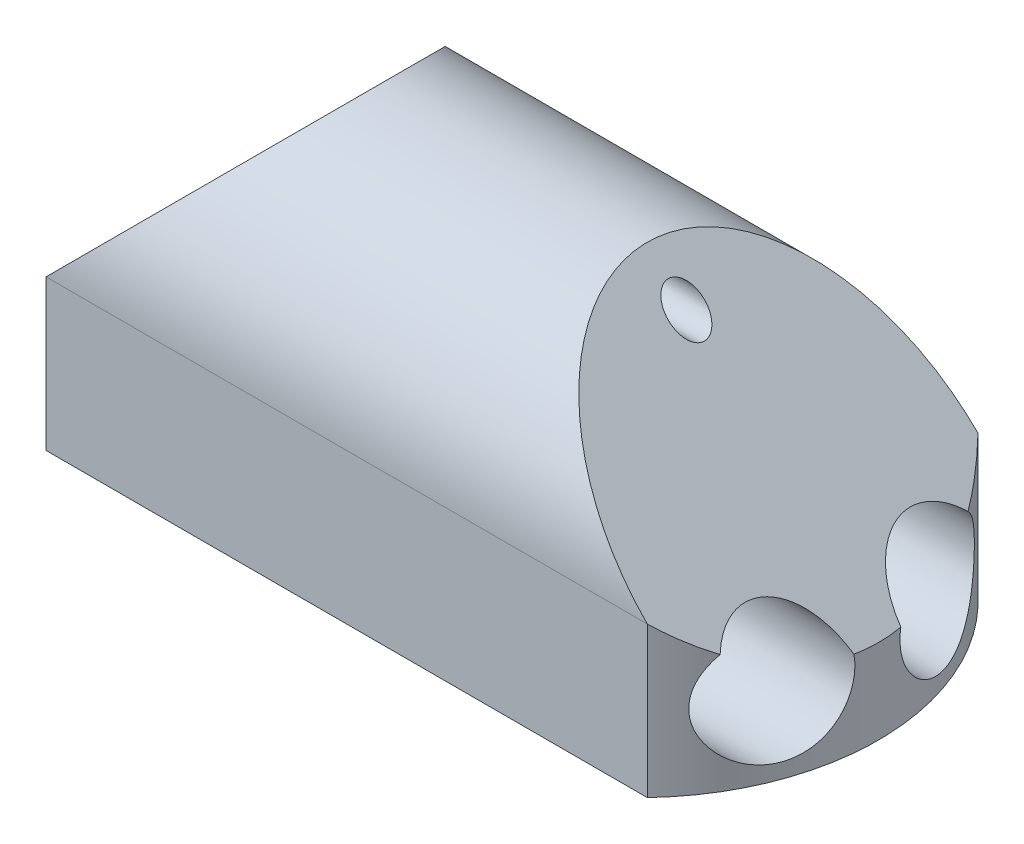
SolidWorks part; units mm, degrees
ref_plane "Front Plane" through (0, 0, 0) normal (0, 0, 1) x (1, 0, 0)
ref_plane "Top Plane" through (0, 0, 0) normal (0, 1, 0) x (1, 0, 0)
ref_plane "Right Plane" through (0, 0, 0) normal (1, 0, 0) x (0, 0, -1)
sketch "Sketch1" plane through (0, 0, 0) normal (0, 1, 0) x (1, 0, 0)
  line L1 (0, 0) -> (-25.4, 0)
  line L2 (0, 0) -> (0, 13.97)
  line L3 (0, 13.97) -> (-25.4, 13.97)
  line L4 (-25.4, 0) -> (-25.4, 13.97)
  dimension "length" = 25.4
  dimension "width" = 13.97
extrude "depth a" add sketch "Sketch1" along normal blind 6.35
sketch "Sketch4" plane through (0, 0, 0) normal (1, 0, 0) x (0, 0, -1)
  line L3 (0, 6.35) -> (13.97, 6.35) construction
  line L4 (0, 6.35) -> (13.97, 6.35)
  arc A0 (0, 6.35) -> (13.97, 6.35) centre (6.985, 6.35) cw
extrude "round extrude" add sketch "Sketch4" against normal up to surface (25.4 mm away) up to face at (-25.4, 3.175, -6.985)
sketch "Sketch5" plane through (0, 0, 0) normal (0, 0, 1) x (1, 0, 0)
  line L0 (0, 6.35) -> (0, 13.335)
  line L1 (0, 13.335) -> (-6.985, 13.335)
  line L2 (0, 13.335) -> (-25.4, 13.335) construction
  line L3 (-6.985, 13.335) -> (0, 6.35)
  line L4 (-12.7, -3.2288) -> (-12.7, 15.9288) construction
  line L6 (-25.4, 6.35) -> (-25.4, 13.335)
  line L7 (-25.4, 13.335) -> (-18.415, 13.335)
  line L8 (-18.415, 13.335) -> (-25.4, 6.35)
  line L9 (-25.4, 6.35) -> (0, 6.35) construction
  point P10 (-12.7, 6.35)
  point P16 (-12.7, 6.35)
  dimension "D1" = 45
extrude "angle cut" cut sketch "Sketch5" against normal through all
sketch "string hole " plane through (0, 0, 0) normal (1, 0, 0) x (0, 0, -1)
  line L0 (6.985, 6.35) -> (6.985, 13.335) construction
  line L1 (13.97, 6.35) -> (0, 6.35) construction
  circle A0 centre (6.985, 11.684) radius 0.762
  arc A1 (13.97, 6.35) -> (0, 6.35) centre (6.985, 6.35) ccw construction
  dimension "D1" = 1.524
  dimension "D2" = 5.334
extrude "string hole cut" cut sketch "string hole " against normal through all
sketch "elastic holes" plane through (0, 0, 0) normal (1, 0, 0) x (0, 0, -1)
  line L1 (13.97, 6.35) -> (0, 6.35) construction
  line L2 (0, 0) -> (13.97, 0) construction
  line L3 (6.985, 0) -> (6.985, 6.35) construction
  line L5 (6.985, 3.175) -> (0, 3.175) construction
  line L7 (0, 6.35) -> (0, 0) construction
  circle A0 centre (3.4925, 3.175) radius 2.54
  circle A1 centre (10.4775, 3.175) radius 2.54
  point P5 (6.985, 6.35)
  point P8 (3.4925, 3.175)
  point P13 (6.985, 3.175)
  point P17 (6.985, 0)
  point P20 (0, 3.175)
  dimension "D1" = 5.08
extrude "elastic hole cut" cut sketch "elastic holes" against normal through all and the other way through all
sketch "guide outie" plane through (0, 0, 0) normal (0, 1, 0) x (1, 0, 0)
  line L0 (0, 13.97) -> (0, 0)
  arc A1 (0, 13.97) -> (0, 0) centre (-7.378, 6.985) cw
  dimension "D1" = 10.16
extrude "guide outie extrude" add sketch "guide outie" along normal up to surface (6.35 mm away)
sketch "Sketch7" plane through (0, 0, 0) normal (-1, 0, 0) x (0, 0, 1)
  circle A0 centre (-3.4925, 3.175) radius 2.54 construction
  circle A1 centre (-10.4775, 3.175) radius 2.54 construction
  circle A2 centre (-3.4925, 3.175) radius 2.54
  circle A3 centre (-10.4775, 3.175) radius 2.54
extrude "elastic hole cut on guide outie" cut sketch "Sketch7" against normal through all
sketch "guide innie" plane through (0, 0, 0) normal (0, 1, 0) x (1, 0, 0)
  line L0 (-25.4, 13.97) -> (-25.4, 0)
  arc A0 (-25.4, 13.97) -> (-25.4, 0) centre (-32.778, 6.985) cw
  dimension "D1" = 10.16
extrude "guide innie cut" cut sketch "guide innie" along normal through all
